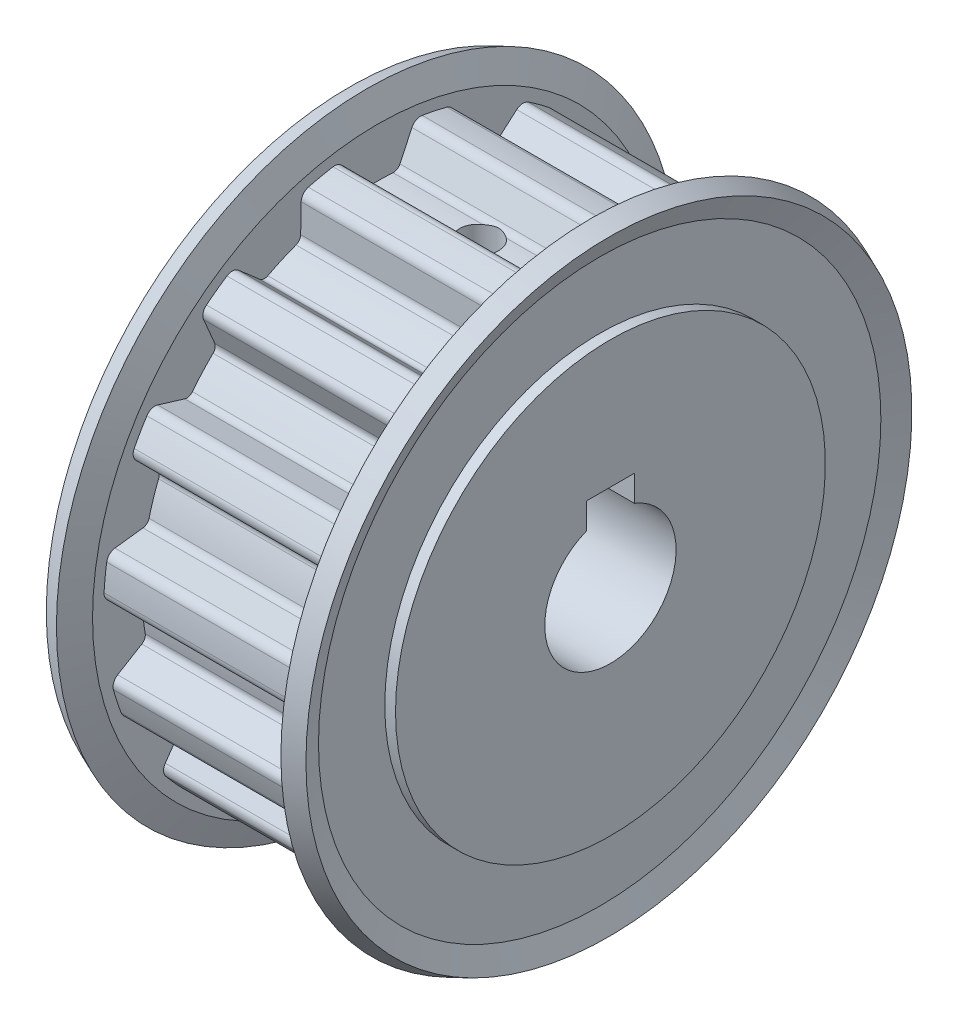
SolidWorks part; units mm, degrees
material "AISI 1020"
ref_plane "Plano frontal" through (0, 0, 0) normal (0, 0, 1) x (1, 0, 0)
ref_plane "Plano superior" through (0, 0, 0) normal (0, 1, 0) x (1, 0, 0)
ref_plane "Plano direito" through (0, 0, 0) normal (1, 0, 0) x (0, 0, -1)
ref_plane "Plane1" through (0, 0, 0) normal (0, 0, 1) x (1, 0, 0)
sketch "Sketch1" plane through (0, 0, 0) normal (0, 0, 1) x (1, 0, 0)
  line L0 (0, 18) -> (0, 5.5)
  line L1 (0, 5.5) -> (37, 5.5)
  line L2 (37, 5.5) -> (37, 6.5)
  line L3 (37, 6.5) -> (22, 6.5)
  line L4 (22, 6.5) -> (22, 18)
  line L5 (22, 18) -> (21.1, 18)
  line L6 (21.1, 18) -> (21.1, 23.5501)
  line L7 (21.1, 23.5501) -> (21.8733, 25.376)
  line L8 (21.8733, 25.376) -> (20.4, 26)
  line L9 (20.4, 26) -> (19.5, 23.875)
  line L10 (19.5, 23.875) -> (19.5, 22.95)
  line L11 (19.5, 22.95) -> (2.5, 22.95)
  line L12 (2.5, 22.95) -> (2.5, 23.875)
  line L13 (2.5, 23.875) -> (1.6, 26)
  line L14 (1.6, 26) -> (0.1267, 25.376)
  line L15 (0.1267, 25.376) -> (0.9, 23.5501)
  line L16 (0.9, 23.5501) -> (0.9, 18)
  line L17 (0.9, 18) -> (0, 18)
  line L18 (37, 0) -> (0, 0) construction
revolve "Revolve1" add sketch "Sketch1" angle 360 about L18
ref_plane "Plane2" through (0, 0, 0) normal (0, 0, 1) x (1, 0, 0)
sketch "Sketch2" plane through (0, 0, 0) normal (0, 0, 1) x (1, 0, 0)
  line L0 (22, 0) -> (22, 18)
  line L1 (22, 18) -> (37, 18)
  line L2 (37, 18) -> (37, 0)
  line L3 (37, 0) -> (22, 0)
  line L4 (37, 0) -> (22, 0) construction
revolve "Cut-Revolve1" cut sketch "Sketch2" angle 360 about L4
ref_plane "Plane3" through (2.5, 0, 0) normal (1, 0, 0) x (0, 0, -1)
sketch "Sketch3" plane through (2.5, 0, 0) normal (1, 0, 0) x (0, 0, -1)
  line L0 (-2.8737, 22.1938) -> (-1.8754, 20.0528)
  line L1 (1.8754, 20.0528) -> (2.8737, 22.1938)
  line L2 (3.7288, 22.6451) -> (3.7288, 30.6)
  line L3 (3.7288, 30.6) -> (-3.7288, 30.6)
  line L4 (-3.7288, 30.6) -> (-3.7288, 22.6451)
  arc A0 (-3.7288, 22.6451) -> (-2.8737, 22.1938) centre (-3.5988, 21.8557) cw
  arc A1 (-1.8754, 20.0528) -> (-1.2923, 19.7077) centre (-1.3316, 20.3064) ccw
  arc A2 (-1.2923, 19.7077) -> (1.2923, 19.7077) centre (0, 0) cw
  arc A3 (1.2923, 19.7077) -> (1.8754, 20.0528) centre (1.3316, 20.3064) ccw
  arc A4 (2.8737, 22.1938) -> (3.7288, 22.6451) centre (3.5988, 21.8557) cw
extrude "Cut-Extrude1" cut sketch "Sketch3" along normal blind 17
ref_plane "Plane4" through (2.5, 0, 0) normal (1, 0, 0) x (0, 0, -1)
sketch "Sketch4" plane through (2.5, 0, 0) normal (1, 0, 0) x (0, 0, -1)
  line L0 (6.4017, 21.4439) -> (6.443, 19.0819)
  line L1 (9.8695, 17.5564) -> (11.6523, 19.1062)
  line L2 (12.617, 19.1707) -> (15.8525, 26.4379)
  line L3 (15.8525, 26.4379) -> (9.0397, 29.4711)
  line L4 (9.0397, 29.4711) -> (5.8042, 22.2039)
  arc A0 (5.8042, 22.2039) -> (6.4017, 21.4439) centre (5.6019, 21.4299) cw
  arc A1 (6.443, 19.0819) -> (6.8352, 18.5295) centre (7.0429, 19.0924) ccw
  arc A2 (6.8352, 18.5295) -> (9.1964, 17.4782) centre (0, 0) cw
  arc A3 (9.1964, 17.4782) -> (9.8695, 17.5564) centre (9.4758, 18.0092) ccw
  arc A4 (11.6523, 19.1062) -> (12.617, 19.1707) centre (12.1772, 18.5024) cw
extrude "Cut-Extrude2" cut sketch "Sketch4" along normal blind 17
ref_plane "Plane5" through (2.5, 0, 0) normal (1, 0, 0) x (0, 0, -1)
sketch "Sketch5" plane through (2.5, 0, 0) normal (1, 0, 0) x (0, 0, -1)
  line L0 (14.5703, 16.9861) -> (13.6473, 14.8116)
  line L1 (16.157, 12.0243) -> (18.4161, 12.7149)
  line L2 (19.3236, 12.3815) -> (25.2353, 17.7044)
  line L3 (25.2353, 17.7044) -> (20.2452, 23.2464)
  line L4 (20.2452, 23.2464) -> (14.3335, 17.9235)
  arc A0 (14.3335, 17.9235) -> (14.5703, 16.9861) centre (13.8339, 17.2987) cw
  arc A1 (13.6473, 14.8116) -> (13.7809, 14.1474) centre (14.1996, 14.5772) ccw
  arc A2 (13.7809, 14.1474) -> (15.5104, 12.2266) centre (0, 0) cw
  arc A3 (15.5104, 12.2266) -> (16.157, 12.0243) centre (15.9816, 12.5981) ccw
  arc A4 (18.4161, 12.7149) -> (19.3236, 12.3815) centre (18.65, 11.9499) cw
extrude "Cut-Extrude3" cut sketch "Sketch5" along normal blind 17
ref_plane "Plane6" through (2.5, 0, 0) normal (1, 0, 0) x (0, 0, -1)
sketch "Sketch6" plane through (2.5, 0, 0) normal (1, 0, 0) x (0, 0, -1)
  line L0 (20.2195, 9.5913) -> (18.4918, 7.9803)
  line L1 (19.6509, 4.4131) -> (21.9956, 4.1252)
  line L2 (22.689, 3.4514) -> (30.2546, 5.9097)
  line L3 (30.2546, 5.9097) -> (27.9501, 13.0022)
  line L4 (27.9501, 13.0022) -> (20.3845, 10.544)
  arc A0 (20.3845, 10.544) -> (20.2195, 9.5913) centre (19.6739, 10.1764) cw
  arc A1 (18.4918, 7.9803) -> (18.3438, 7.3191) centre (18.901, 7.5414) ccw
  arc A2 (18.3438, 7.3191) -> (19.1425, 4.8609) centre (0, 0) cw
  arc A3 (19.1425, 4.8609) -> (19.6509, 4.4131) centre (19.724, 5.0086) ccw
  arc A4 (21.9956, 4.1252) -> (22.689, 3.4514) centre (21.8981, 3.3311) cw
extrude "Cut-Extrude4" cut sketch "Sketch6" along normal blind 17
ref_plane "Plane7" through (2.5, 0, 0) normal (1, 0, 0) x (0, 0, -1)
sketch "Sketch7" plane through (2.5, 0, 0) normal (1, 0, 0) x (0, 0, -1)
  line L0 (22.3726, 0.5381) -> (20.139, -0.231)
  line L1 (19.7469, -3.9612) -> (21.7718, -5.1779)
  line L2 (22.1312, -6.0754) -> (30.0426, -6.9069)
  line L3 (30.0426, -6.9069) -> (30.8221, 0.5098)
  line L4 (30.8221, 0.5098) -> (22.9108, 1.3413)
  arc A0 (22.9108, 1.3413) -> (22.3726, 0.5381) centre (22.1121, 1.2945) cw
  arc A1 (20.139, -0.231) -> (19.7348, -0.7748) centre (20.3343, -0.7983) ccw
  arc A2 (19.7348, -0.7748) -> (19.4646, -3.3453) centre (0, 0) cw
  arc A3 (19.4646, -3.3453) -> (19.7469, -3.9612) centre (20.056, -3.4469) ccw
  arc A4 (21.7718, -5.1779) -> (22.1312, -6.0754) centre (21.3598, -5.8636) cw
extrude "Cut-Extrude5" cut sketch "Sketch7" along normal blind 17
ref_plane "Plane8" through (2.5, 0, 0) normal (1, 0, 0) x (0, 0, -1)
sketch "Sketch8" plane through (2.5, 0, 0) normal (1, 0, 0) x (0, 0, -1)
  line L0 (20.6573, -8.6082) -> (18.3039, -8.4023)
  line L1 (16.4286, -11.6505) -> (17.7835, -13.5856)
  line L2 (17.7468, -14.5517) -> (24.636, -18.5292)
  line L3 (24.636, -18.5292) -> (28.3648, -12.0708)
  line L4 (28.3648, -12.0708) -> (21.4756, -8.0933)
  arc A0 (21.4756, -8.0933) -> (20.6573, -8.6082) centre (20.727, -7.8112) cw
  arc A1 (18.3039, -8.4023) -> (17.7135, -8.7346) centre (18.2516, -9) ccw
  arc A2 (17.7135, -8.7346) -> (16.4212, -10.973) centre (0, 0) cw
  arc A3 (16.4212, -10.973) -> (16.4286, -11.6505) centre (16.92, -11.3064) ccw
  arc A4 (17.7835, -13.5856) -> (17.7468, -14.5517) centre (17.1282, -14.0445) cw
extrude "Cut-Extrude6" cut sketch "Sketch8" along normal blind 17
ref_plane "Plane9" through (2.5, 0, 0) normal (1, 0, 0) x (0, 0, -1)
sketch "Sketch9" plane through (2.5, 0, 0) normal (1, 0, 0) x (0, 0, -1)
  line L0 (15.3701, -16.266) -> (13.304, -15.1207)
  line L1 (10.2695, -17.3254) -> (10.7203, -19.6443)
  line L2 (10.2938, -20.512) -> (14.9696, -26.9476)
  line L3 (14.9696, -26.9476) -> (21.0029, -22.5642)
  line L4 (21.0029, -22.5642) -> (16.3271, -16.1285)
  arc A0 (16.3271, -16.1285) -> (15.3701, -16.266) centre (15.7579, -15.5663) cw
  arc A1 (13.304, -15.1207) -> (12.6294, -15.1842) centre (13.0131, -15.6455) ccw
  arc A2 (12.6294, -15.1842) -> (10.5384, -16.7035) centre (0, 0) cw
  arc A3 (10.5384, -16.7035) -> (10.2695, -17.3254) centre (10.8585, -17.2109) ccw
  arc A4 (10.7203, -19.6443) -> (10.2938, -20.512) centre (9.935, -19.7969) cw
extrude "Cut-Extrude7" cut sketch "Sketch9" along normal blind 17
ref_plane "Plane10" through (2.5, 0, 0) normal (1, 0, 0) x (0, 0, -1)
sketch "Sketch10" plane through (2.5, 0, 0) normal (1, 0, 0) x (0, 0, -1)
  line L0 (7.4253, -21.1113) -> (6.0036, -19.2247)
  line L1 (2.3348, -20.0045) -> (1.8034, -22.3063)
  line L2 (1.0609, -22.9255) -> (2.7148, -30.7066)
  line L3 (2.7148, -30.7066) -> (10.0094, -29.1561)
  line L4 (10.0094, -29.1561) -> (8.3555, -21.375)
  arc A0 (8.3555, -21.375) -> (7.4253, -21.1113) centre (8.0642, -20.6299) cw
  arc A1 (6.0036, -19.2247) -> (5.3616, -19.0083) centre (5.5244, -19.5858) ccw
  arc A2 (5.3616, -19.0083) -> (2.8334, -19.5457) centre (0, 0) cw
  arc A3 (2.8334, -19.5457) -> (2.3348, -20.0045) centre (2.9194, -20.1395) ccw
  arc A4 (1.8034, -22.3063) -> (1.0609, -22.9255) centre (1.0239, -22.1263) cw
extrude "Cut-Extrude8" cut sketch "Sketch10" along normal blind 17
ref_plane "Plane11" through (2.5, 0, 0) normal (1, 0, 0) x (0, 0, -1)
sketch "Sketch11" plane through (2.5, 0, 0) normal (1, 0, 0) x (0, 0, -1)
  line L0 (-1.8034, -22.3063) -> (-2.3348, -20.0045)
  line L1 (-6.0036, -19.2247) -> (-7.4253, -21.1113)
  line L2 (-8.3555, -21.375) -> (-10.0094, -29.1561)
  line L3 (-10.0094, -29.1561) -> (-2.7148, -30.7066)
  line L4 (-2.7148, -30.7066) -> (-1.0609, -22.9255)
  arc A0 (-1.0609, -22.9255) -> (-1.8034, -22.3063) centre (-1.0239, -22.1263) cw
  arc A1 (-2.3348, -20.0045) -> (-2.8334, -19.5457) centre (-2.9194, -20.1395) ccw
  arc A2 (-2.8334, -19.5457) -> (-5.3616, -19.0083) centre (0, 0) cw
  arc A3 (-5.3616, -19.0083) -> (-6.0036, -19.2247) centre (-5.5244, -19.5858) ccw
  arc A4 (-7.4253, -21.1113) -> (-8.3555, -21.375) centre (-8.0642, -20.6299) cw
extrude "Cut-Extrude9" cut sketch "Sketch11" along normal blind 17
ref_plane "Plane12" through (2.5, 0, 0) normal (1, 0, 0) x (0, 0, -1)
sketch "Sketch12" plane through (2.5, 0, 0) normal (1, 0, 0) x (0, 0, -1)
  line L0 (-10.7203, -19.6443) -> (-10.2695, -17.3254)
  line L1 (-13.304, -15.1207) -> (-15.3701, -16.266)
  line L2 (-16.3271, -16.1285) -> (-21.0029, -22.5642)
  line L3 (-21.0029, -22.5642) -> (-14.9696, -26.9476)
  line L4 (-14.9696, -26.9476) -> (-10.2938, -20.512)
  arc A0 (-10.2938, -20.512) -> (-10.7203, -19.6443) centre (-9.935, -19.7969) cw
  arc A1 (-10.2695, -17.3254) -> (-10.5384, -16.7035) centre (-10.8585, -17.2109) ccw
  arc A2 (-10.5384, -16.7035) -> (-12.6294, -15.1842) centre (0, 0) cw
  arc A3 (-12.6294, -15.1842) -> (-13.304, -15.1207) centre (-13.0131, -15.6455) ccw
  arc A4 (-15.3701, -16.266) -> (-16.3271, -16.1285) centre (-15.7579, -15.5663) cw
extrude "Cut-Extrude10" cut sketch "Sketch12" along normal blind 17
ref_plane "Plane13" through (2.5, 0, 0) normal (1, 0, 0) x (0, 0, -1)
sketch "Sketch13" plane through (2.5, 0, 0) normal (1, 0, 0) x (0, 0, -1)
  line L0 (-17.7835, -13.5856) -> (-16.4286, -11.6505)
  line L1 (-18.3039, -8.4023) -> (-20.6573, -8.6082)
  line L2 (-21.4756, -8.0933) -> (-28.3648, -12.0708)
  line L3 (-28.3648, -12.0708) -> (-24.636, -18.5292)
  line L4 (-24.636, -18.5292) -> (-17.7468, -14.5517)
  arc A0 (-17.7468, -14.5517) -> (-17.7835, -13.5856) centre (-17.1282, -14.0445) cw
  arc A1 (-16.4286, -11.6505) -> (-16.4212, -10.973) centre (-16.92, -11.3064) ccw
  arc A2 (-16.4212, -10.973) -> (-17.7135, -8.7346) centre (0, 0) cw
  arc A3 (-17.7135, -8.7346) -> (-18.3039, -8.4023) centre (-18.2516, -9) ccw
  arc A4 (-20.6573, -8.6082) -> (-21.4756, -8.0933) centre (-20.727, -7.8112) cw
extrude "Cut-Extrude11" cut sketch "Sketch13" along normal blind 17
ref_plane "Plane14" through (2.5, 0, 0) normal (1, 0, 0) x (0, 0, -1)
sketch "Sketch14" plane through (2.5, 0, 0) normal (1, 0, 0) x (0, 0, -1)
  line L0 (-21.7718, -5.1779) -> (-19.7469, -3.9612)
  line L1 (-20.139, -0.231) -> (-22.3726, 0.5381)
  line L2 (-22.9108, 1.3413) -> (-30.8221, 0.5098)
  line L3 (-30.8221, 0.5098) -> (-30.0426, -6.9069)
  line L4 (-30.0426, -6.9069) -> (-22.1312, -6.0754)
  arc A0 (-22.1312, -6.0754) -> (-21.7718, -5.1779) centre (-21.3598, -5.8636) cw
  arc A1 (-19.7469, -3.9612) -> (-19.4646, -3.3453) centre (-20.056, -3.4469) ccw
  arc A2 (-19.4646, -3.3453) -> (-19.7348, -0.7748) centre (0, 0) cw
  arc A3 (-19.7348, -0.7748) -> (-20.139, -0.231) centre (-20.3343, -0.7983) ccw
  arc A4 (-22.3726, 0.5381) -> (-22.9108, 1.3413) centre (-22.1121, 1.2945) cw
extrude "Cut-Extrude12" cut sketch "Sketch14" along normal blind 17
ref_plane "Plane15" through (2.5, 0, 0) normal (1, 0, 0) x (0, 0, -1)
sketch "Sketch15" plane through (2.5, 0, 0) normal (1, 0, 0) x (0, 0, -1)
  line L0 (-21.9956, 4.1252) -> (-19.6509, 4.4131)
  line L1 (-18.4918, 7.9803) -> (-20.2195, 9.5913)
  line L2 (-20.3845, 10.544) -> (-27.9501, 13.0022)
  line L3 (-27.9501, 13.0022) -> (-30.2546, 5.9097)
  line L4 (-30.2546, 5.9097) -> (-22.689, 3.4514)
  arc A0 (-22.689, 3.4514) -> (-21.9956, 4.1252) centre (-21.8981, 3.3311) cw
  arc A1 (-19.6509, 4.4131) -> (-19.1425, 4.8609) centre (-19.724, 5.0086) ccw
  arc A2 (-19.1425, 4.8609) -> (-18.3438, 7.3191) centre (0, 0) cw
  arc A3 (-18.3438, 7.3191) -> (-18.4918, 7.9803) centre (-18.901, 7.5414) ccw
  arc A4 (-20.2195, 9.5913) -> (-20.3845, 10.544) centre (-19.6739, 10.1764) cw
extrude "Cut-Extrude13" cut sketch "Sketch15" along normal blind 17
ref_plane "Plane16" through (2.5, 0, 0) normal (1, 0, 0) x (0, 0, -1)
sketch "Sketch16" plane through (2.5, 0, 0) normal (1, 0, 0) x (0, 0, -1)
  line L0 (-18.4161, 12.7149) -> (-16.157, 12.0243)
  line L1 (-13.6473, 14.8116) -> (-14.5703, 16.9861)
  line L2 (-14.3335, 17.9235) -> (-20.2452, 23.2464)
  line L3 (-20.2452, 23.2464) -> (-25.2353, 17.7044)
  line L4 (-25.2353, 17.7044) -> (-19.3236, 12.3815)
  arc A0 (-19.3236, 12.3815) -> (-18.4161, 12.7149) centre (-18.65, 11.9499) cw
  arc A1 (-16.157, 12.0243) -> (-15.5104, 12.2266) centre (-15.9816, 12.5981) ccw
  arc A2 (-15.5104, 12.2266) -> (-13.7809, 14.1474) centre (0, 0) cw
  arc A3 (-13.7809, 14.1474) -> (-13.6473, 14.8116) centre (-14.1996, 14.5772) ccw
  arc A4 (-14.5703, 16.9861) -> (-14.3335, 17.9235) centre (-13.8339, 17.2987) cw
extrude "Cut-Extrude14" cut sketch "Sketch16" along normal blind 17
ref_plane "Plane17" through (2.5, 0, 0) normal (1, 0, 0) x (0, 0, -1)
sketch "Sketch17" plane through (2.5, 0, 0) normal (1, 0, 0) x (0, 0, -1)
  line L0 (-11.6523, 19.1062) -> (-9.8695, 17.5564)
  line L1 (-6.443, 19.0819) -> (-6.4017, 21.4439)
  line L2 (-5.8042, 22.2039) -> (-9.0397, 29.4711)
  line L3 (-9.0397, 29.4711) -> (-15.8525, 26.4379)
  line L4 (-15.8525, 26.4379) -> (-12.617, 19.1707)
  arc A0 (-12.617, 19.1707) -> (-11.6523, 19.1062) centre (-12.1772, 18.5024) cw
  arc A1 (-9.8695, 17.5564) -> (-9.1964, 17.4782) centre (-9.4758, 18.0092) ccw
  arc A2 (-9.1964, 17.4782) -> (-6.8352, 18.5295) centre (0, 0) cw
  arc A3 (-6.8352, 18.5295) -> (-6.443, 19.0819) centre (-7.0429, 19.0924) ccw
  arc A4 (-6.4017, 21.4439) -> (-5.8042, 22.2039) centre (-5.6019, 21.4299) cw
extrude "Cut-Extrude15" cut sketch "Sketch17" along normal blind 17
ref_plane "Plane18" through (11, 0, 0) normal (1, 0, 0) x (0, 0, -1)
sketch "Sketch18" plane through (11, 0, 0) normal (1, 0, 0) x (0, 0, -1)
  line L0 (0, 22.95) -> (1.621, 22.95)
  line L1 (1.621, 22.95) -> (1.621, 7.3)
  line L2 (1.621, 7.3) -> (0, 7.3)
  line L3 (0, 7.3) -> (0, 22.95)
  line L4 (0, 7.3) -> (0, 22.95) construction
revolve "Cut-Revolve2" cut sketch "Sketch18" angle 360 about L4
ref_plane "Plane19" through (11, 0, 0) normal (1, 0, 0) x (0, 0, -1)
sketch "Sketch19" plane through (11, 0, 0) normal (1, 0, 0) x (0, 0, -1)
  line L0 (19.8753, -11.475) -> (19.0648, -12.8788)
  line L1 (19.0648, -12.8788) -> (3.6266, -3.9656)
  line L2 (3.6266, -3.9656) -> (4.4371, -2.5617)
  line L3 (4.4371, -2.5617) -> (19.8753, -11.475)
  line L4 (4.4371, -2.5617) -> (19.8753, -11.475) construction
revolve "Cut-Revolve3" cut sketch "Sketch19" angle 360 about L4
ref_plane "Plane20" through (0, 0, 0) normal (1, 0, 0) x (0, 0, -1)
sketch "Sketch20" plane through (0, 0, 0) normal (1, 0, 0) x (0, 0, -1)
  line L0 (-2, 0) -> (2, 0)
  line L1 (2, 0) -> (2, 7.3)
  line L2 (2, 7.3) -> (-2, 7.3)
  line L3 (-2, 7.3) -> (-2, 0)
extrude "Cut-Extrude16" cut sketch "Sketch20" along normal blind 37
